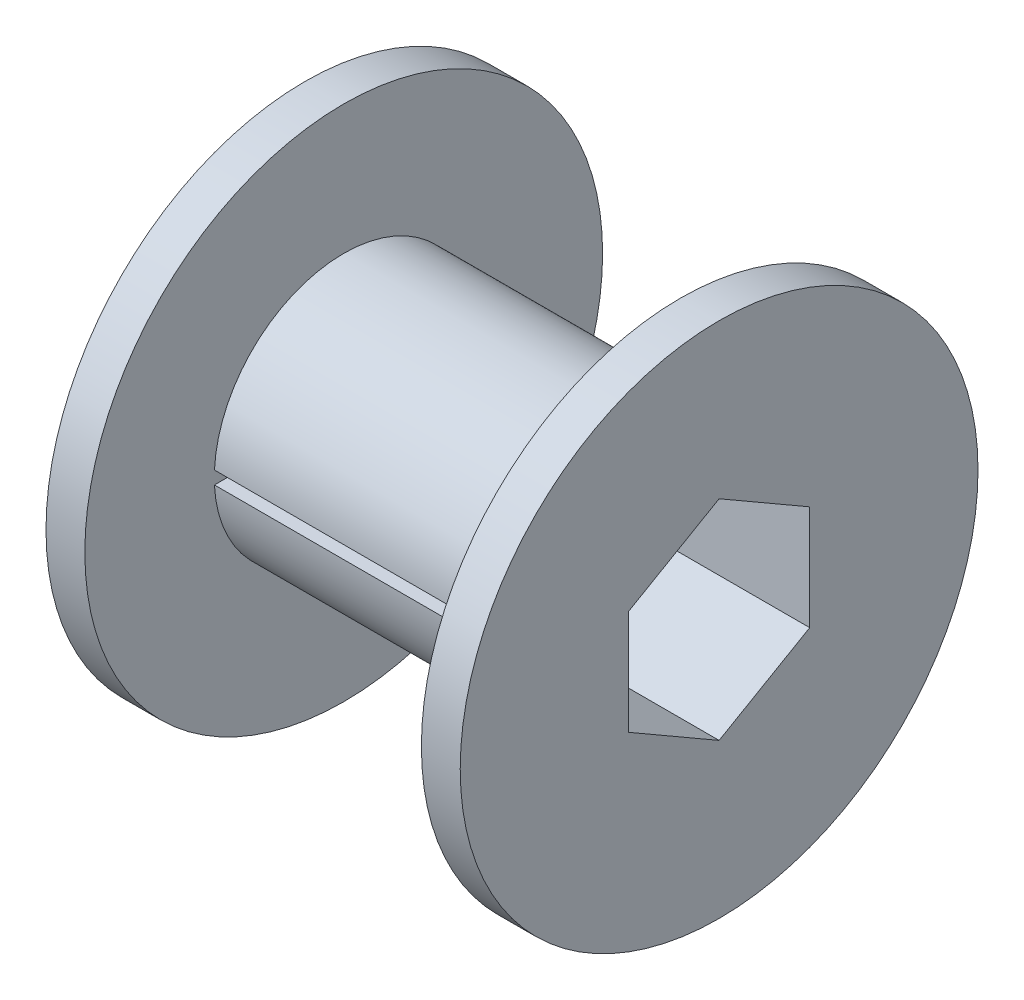
SolidWorks part; units mm, degrees
ref_plane "Front Plane" through (0, 0, 0) normal (0, 0, 1) x (1, 0, 0)
ref_plane "Top Plane" through (0, 0, 0) normal (0, 1, 0) x (1, 0, 0)
ref_plane "Right Plane" through (0, 0, 0) normal (1, 0, 0) x (0, 0, -1)
sketch "Sketch1" plane through (0, 0, 0) normal (1, 0, 0) x (0, 0, -1)
  circle A0 centre (0, 0) radius 2.5
  dimension "D1" = 5
extrude "Boss-Extrude1" add sketch "Sketch1" along normal mid plane 8
sketch "Sketch2" plane through (4, 0, 0) normal (1, 0, 0) x (0, 0, -1)
  circle A0 centre (0, 0) radius 5
  dimension "D1" = 10
extrude "Boss-Extrude2" add sketch "Sketch2" against normal blind 0.75
mirror "Mirror1" about plane through (0, 0, 0) normal (1, 0, 0) of "Boss-Extrude2"
sketch "Sketch3" plane through (0, 0, 0) normal (1, 0, 0) x (0, 0, -1)
  line L0 (1.75, 0) -> (1.75, 1.0104)
  line L1 (1.6, 0) -> (1.6, 0.9238) construction
  line L2 (1.6, -0.9238) -> (1.6, 0) construction
  line L3 (0.8, -1.3856) -> (1.6, -0.9238) construction
  line L4 (0, -1.8475) -> (0.8, -1.3856) construction
  line L5 (-0.8, -1.3856) -> (0, -1.8475) construction
  line L6 (-1.6, -0.9238) -> (-0.8, -1.3856) construction
  line L7 (-1.6, 0) -> (-1.6, -0.9238) construction
  line L8 (-1.6, 0.9238) -> (-1.6, 0) construction
  line L9 (-0.8, 1.3856) -> (-1.6, 0.9238) construction
  line L10 (0, 1.8475) -> (-0.8, 1.3856) construction
  line L11 (0.8, 1.3856) -> (0, 1.8475) construction
  line L12 (1.6, 0.9238) -> (0.8, 1.3856) construction
  line L13 (1.6, 0) -> (1.6, 0.9238) construction
  line L14 (1.6, -0.9238) -> (1.6, 0) construction
  line L15 (0.8, -1.3856) -> (1.6, -0.9238) construction
  line L16 (0, -1.8475) -> (0.8, -1.3856) construction
  line L17 (-0.8, -1.3856) -> (0, -1.8475) construction
  line L18 (-1.6, -0.9238) -> (-0.8, -1.3856) construction
  line L19 (-1.6, 0) -> (-1.6, -0.9238) construction
  line L20 (-1.6, 0.9238) -> (-1.6, 0) construction
  line L21 (-0.8, 1.3856) -> (-1.6, 0.9238) construction
  line L22 (0, 1.8475) -> (-0.8, 1.3856) construction
  line L23 (0.8, 1.3856) -> (0, 1.8475) construction
  line L24 (1.6, 0.9238) -> (0.8, 1.3856) construction
  line L25 (1.75, 1.0104) -> (0.875, 1.5155)
  line L26 (0.875, 1.5155) -> (0, 2.0207)
  line L27 (0, 2.0207) -> (-0.875, 1.5155)
  line L28 (-0.875, 1.5155) -> (-1.75, 1.0104)
  line L29 (-1.75, 1.0104) -> (-1.75, 0)
  line L30 (-1.75, 0) -> (-1.75, -1.0104)
  line L31 (-1.75, -1.0104) -> (-0.875, -1.5155)
  line L32 (-0.875, -1.5155) -> (0, -2.0207)
  line L33 (0, -2.0207) -> (0.875, -1.5155)
  line L34 (0.875, -1.5155) -> (1.75, -1.0104)
  line L35 (1.75, -1.0104) -> (1.75, 0)
  dimension "D1" = 0.15
extrude "M1.6 Nut" cut sketch "Sketch3" against normal through all both and the other way through all
sketch "Sketch5" plane through (0, 0, 0) normal (0, 0, 1) x (1, 0, 0)
  line L0 (3.25, 2.5) -> (3.25, -2.5) construction
  line L1 (3.25, 0.125) -> (-3.25, 0.125)
  line L2 (3.25, 0.125) -> (3.25, -0.125)
  line L3 (3.25, -0.125) -> (-3.25, -0.125)
  line L12 (-3.25, 0.125) -> (-3.25, -0.125)
  line L13 (3.25, 0.125) -> (-3.25, -0.125) construction
  line L14 (3.25, -0.125) -> (-3.25, 0.125) construction
  point P2 (0, 0)
  dimension "D1" = 0.25
extrude "Cut-Extrude1" cut sketch "Sketch5" along normal through all
